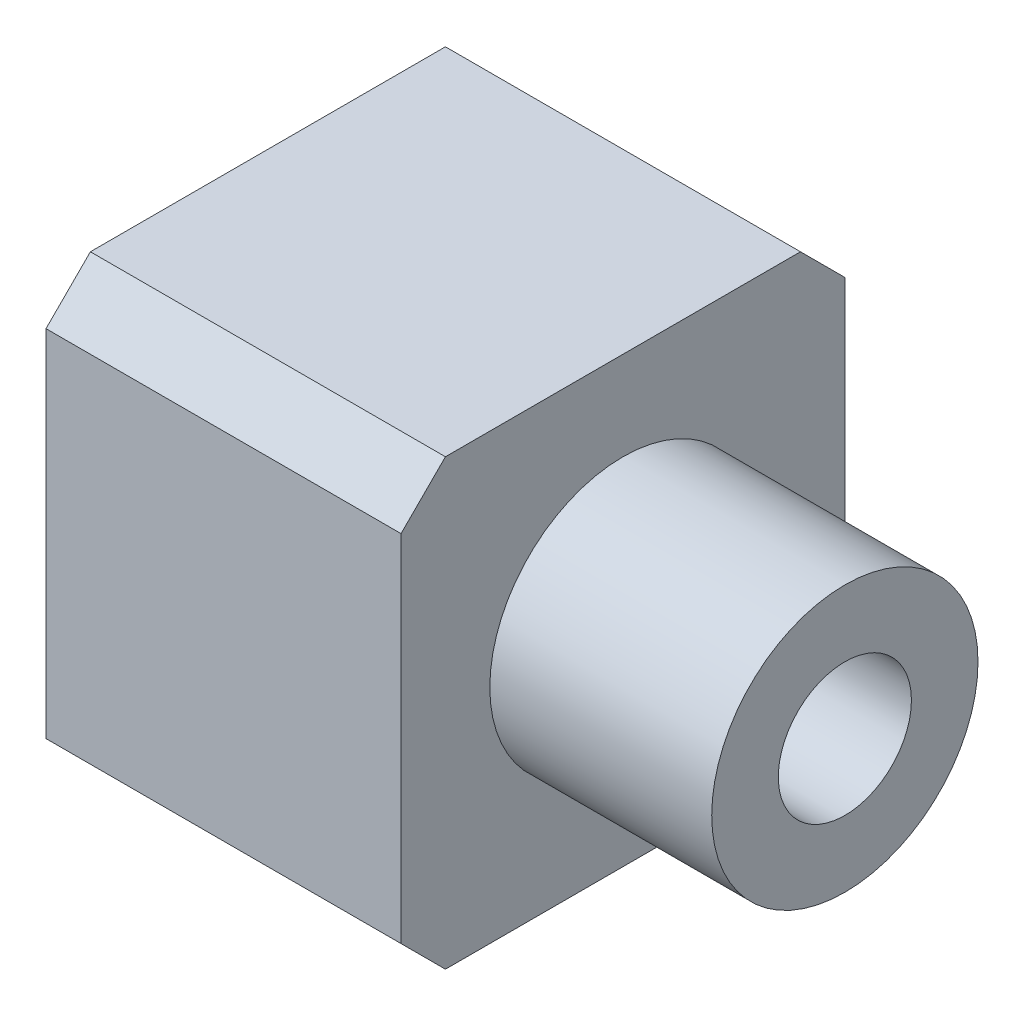
SolidWorks part; units mm, degrees
ref_plane "Front Plane" through (0, 0, 0) normal (0, 0, 1) x (1, 0, 0)
ref_plane "Top Plane" through (0, 0, 0) normal (0, 1, 0) x (1, 0, 0)
ref_plane "Right Plane" through (0, 0, 0) normal (1, 0, 0) x (0, 0, -1)
sketch "Sketch1" plane through (0, 0, 0) normal (1, 0, 0) x (0, 0, -1)
  line L5 (5, -5) -> (-5, -5)
  line L6 (5, -5) -> (5, 5)
  line L7 (5, 5) -> (-5, 5)
  line L8 (-5, -5) -> (-5, 5)
  line L9 (5, -5) -> (-5, 5) construction
  line L10 (5, 5) -> (-5, -5) construction
  point P0 (0, 0)
  dimension "D1" = 10
  dimension "D2" = 10
extrude "Boss-Extrude1" add sketch "Sketch1" against normal blind 15
sketch "Sketch2" plane through (0, 0, 0) normal (1, 0, 0) x (0, 0, -1)
  circle A0 centre (0, 0) radius 3
  circle A1 centre (0, 0) radius 15.3536
  dimension "D1" = 6
extrude "Cut-Extrude1" cut sketch "Sketch2" against normal blind 5
sketch "Sketch3" plane through (-15, 0, 0) normal (-1, 0, 0) x (0, 0, 1)
  circle A0 centre (0, 0) radius 3
  circle A1 centre (0, 0) radius 15.6354
  dimension "D1" = 6
extrude "Cut-Extrude2" cut sketch "Sketch3" against normal blind 2
sketch "Sketch4" plane through (0, 0, 0) normal (1, 0, 0) x (0, 0, -1)
  circle A0 centre (0, 0) radius 1.5
  dimension "D1" = 3
extrude "Cut-Extrude3" cut sketch "Sketch4" against normal through all
chamfer "Chamfer1" distance 1 angle 45 4 edges at (-9, -5, -5) (-9, 5, 5) (-9, -5, 5) (-9, 5, -5)
sketch "Sketch5" plane through (0, 0, 0) normal (0, 0, -1) x (-1, 0, 0)
  line L0 (0, 0) -> (9, 0) construction
  line L1 (0, 3) -> (0, -3) construction
  circle A0 centre (9, 0) radius 1.5
  dimension "D1" = 3
  dimension "D2" = 9
extrude "Cut-Extrude4" cut sketch "Sketch5" against normal blind 2 from offset 5
